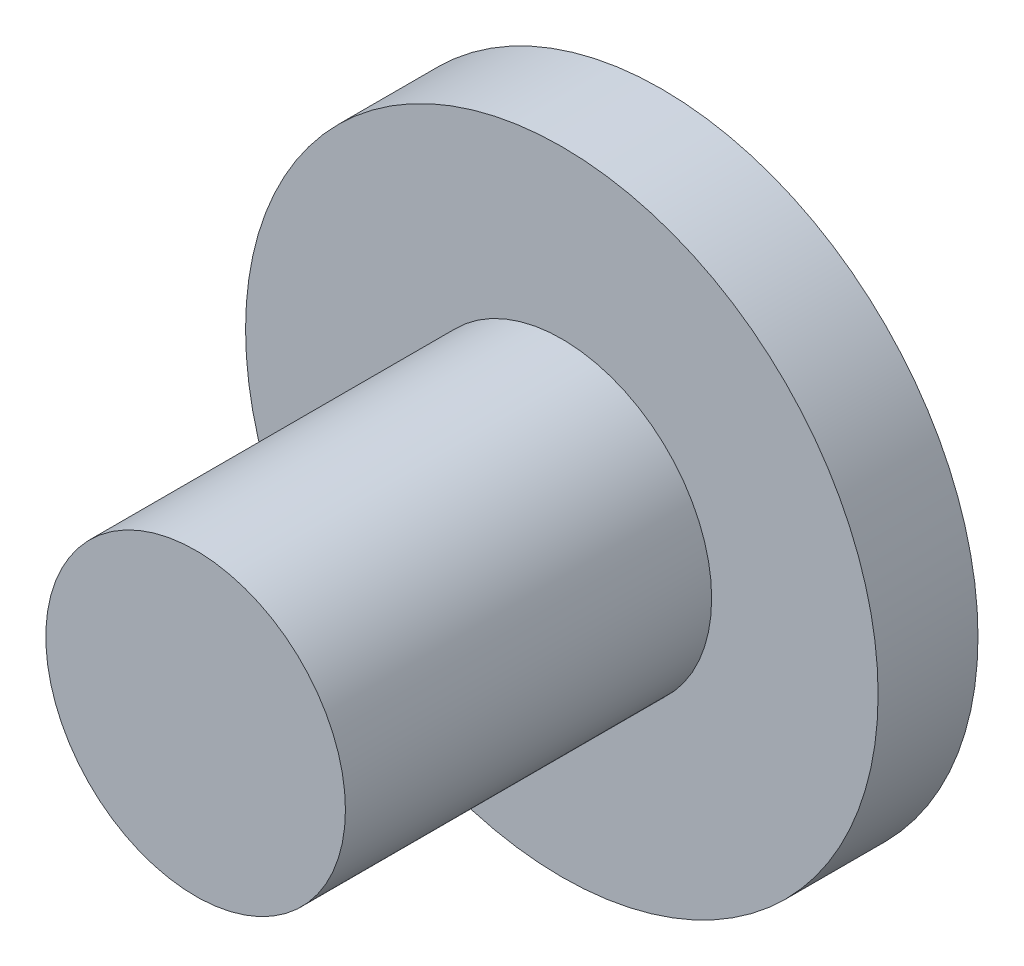
SolidWorks part; units mm, degrees
ref_plane "前视基准面" through (0, 0, 0) normal (0, 0, 1) x (1, 0, 0)
ref_plane "上视基准面" through (0, 0, 0) normal (0, 1, 0) x (1, 0, 0)
ref_plane "右视基准面" through (0, 0, 0) normal (1, 0, 0) x (0, 0, -1)
sketch "草图1" plane through (0, 0, 0) normal (0, 0, 1) x (1, 0, 0)
  circle A0 centre (0, 0) radius 4.75
  dimension "D1" = 9.5
extrude "凸台-拉伸1" add sketch "草图1" along normal blind 1.5
sketch "草图2" plane through (0, 0, 1.5) normal (0, 0, 1) x (1, 0, 0)
  circle A0 centre (0, 0) radius 2.25
  dimension "D1" = 4.5
extrude "凸台-拉伸2" add sketch "草图2" along normal blind 5.5
